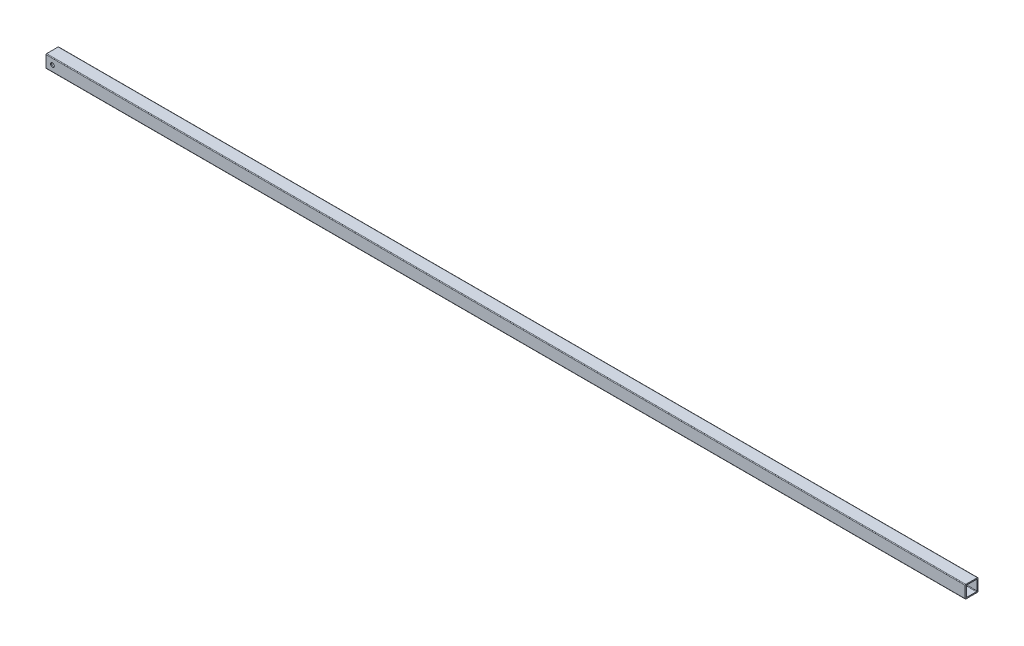
SolidWorks part; units mm, degrees
ref_plane "Front" through (0, 0, 0) normal (0, 0, 1) x (1, 0, 0)
ref_plane "Top" through (0, 0, 0) normal (0, 1, 0) x (1, 0, 0)
ref_plane "Right" through (0, 0, 0) normal (1, 0, 0) x (0, 0, -1)
sketch "Sketch1" plane through (0, 0, 0) normal (1, 0, 0) x (0, 0, -1)
  line L0 (-10.5918, 0) -> (-12.7, 0) construction
  line L1 (11.43, -12.7) -> (-11.43, -12.7) construction
  line L2 (12.7, -11.43) -> (12.7, 11.43) construction
  line L3 (11.43, 12.7) -> (-11.43, 12.7) construction
  line L4 (-12.7, -11.43) -> (-12.7, 11.43) construction
  line L5 (12.7, -12.7) -> (-12.7, 12.7) construction
  line L6 (12.7, 12.7) -> (-12.7, -12.7) construction
  line L7 (9.5326, 10.5918) -> (-9.5326, 10.5918) construction
  line L8 (10.5918, 9.5326) -> (10.5918, -9.5326) construction
  line L9 (9.5326, -10.5918) -> (-9.5326, -10.5918) construction
  line L10 (-10.5918, 9.5326) -> (-10.5918, -9.5326) construction
  line L11 (10.5918, 10.5918) -> (-10.5918, -10.5918) construction
  line L12 (10.5918, -10.5918) -> (-10.5918, 10.5918) construction
  line L13 (0, -10.5918) -> (0, -12.7) construction
  line L14 (10.5918, -9.5326) -> (10.5918, -12.7) construction
  line L15 (10.5918, 0) -> (12.7, 0) construction
  line L16 (10.5918, -12.7) -> (12.7, -12.7) construction
  arc A0 (-9.5326, -10.5918) -> (-10.5918, -9.5326) centre (-9.5326, -9.5326) cw construction
  arc A1 (10.5918, -9.5326) -> (9.5326, -10.5918) centre (9.5326, -9.5326) cw construction
  arc A2 (9.5326, 10.5918) -> (10.5918, 9.5326) centre (9.5326, 9.5326) cw construction
  arc A3 (-9.5326, 10.5918) -> (-10.5918, 9.5326) centre (-9.5326, 9.5326) ccw construction
  arc A4 (11.43, -12.7) -> (12.7, -11.43) centre (11.43, -11.43) ccw construction
  arc A5 (12.7, 11.43) -> (11.43, 12.7) centre (11.43, 11.43) ccw construction
  arc A6 (-11.43, 12.7) -> (-12.7, 11.43) centre (-11.43, 11.43) ccw construction
  arc A7 (-11.43, -12.7) -> (-12.7, -11.43) centre (-11.43, -11.43) cw construction
  point P0 (0, 0)
  point P6 (0, 0)
  dimension "D2" = 1.0592
  dimension "D3" = 1.27
  dimension "Outside Width" = 25.4
  dimension "Ouside Height" = 25.4
  dimension "Inside Height" = 21.1836
  dimension "Wall Thickness" = 2.1082
sketch "Sketch2" plane through (0, 0, 0) normal (0, 0, 1) x (1, 0, 0)
  line L0 (-914.4, 0) -> (914.4, 0) construction
  point P3 (-891.1082, 0)
  point P4 (891.1082, 0)
  dimension "Length" = 1828.8
  dimension "D1" = 23.2918
  dimension "D2" = 23.2918
sketch "Sketch4" plane through (0, 0, 0) normal (1, 0, 0) x (0, 0, -1)
  line L8 (12.7, -11.43) -> (12.7, 11.43)
  line L9 (11.43, 12.7) -> (-11.43, 12.7)
  line L10 (-12.7, -11.43) -> (-12.7, 11.43)
  line L11 (11.43, -12.7) -> (-11.43, -12.7)
  line L12 (10.5918, 9.5326) -> (10.5918, -9.5326)
  line L13 (9.5326, -10.5918) -> (-9.5326, -10.5918)
  line L14 (-10.5918, 9.5326) -> (-10.5918, -9.5326)
  line L15 (9.5326, 10.5918) -> (-9.5326, 10.5918)
  arc A8 (12.7, 11.43) -> (11.43, 12.7) centre (11.43, 11.43) ccw
  arc A9 (-11.43, 12.7) -> (-12.7, 11.43) centre (-11.43, 11.43) ccw
  arc A10 (-12.7, -11.43) -> (-11.43, -12.7) centre (-11.43, -11.43) ccw
  arc A11 (11.43, -12.7) -> (12.7, -11.43) centre (11.43, -11.43) ccw
  arc A12 (9.5326, -10.5918) -> (10.5918, -9.5326) centre (9.5326, -9.5326) ccw
  arc A13 (-10.5918, -9.5326) -> (-9.5326, -10.5918) centre (-9.5326, -9.5326) ccw
  arc A14 (-9.5326, 10.5918) -> (-10.5918, 9.5326) centre (-9.5326, 9.5326) ccw
  arc A15 (10.5918, 9.5326) -> (9.5326, 10.5918) centre (9.5326, 9.5326) ccw
extrude "Boss-Extrude1" add sketch "Sketch4" along normal up to vertex (914.4 mm away) and the other way up to vertex (914.4 mm away)
sketch "Sketch5" plane through (0, 0, 12.7) normal (0, 0, 1) x (1, 0, 0)
  line L0 (-914.4, 11.43) -> (-914.4, -11.43) construction
  line L1 (914.4, 12.7) -> (-914.4, 12.7) construction
  circle A0 centre (-901.7, 0) radius 3.81
  dimension "D2" = 7.62
  dimension "D1" = 12.7
  dimension "D3" = 12.7
extrude "Cut-Extrude1" cut sketch "Sketch5" against normal through all
equation "\"D3@Sketch1\"=\"Outside Width@Sketch1\"*.05"
equation "\"D2@Sketch1\" = \"Inside Height@Sketch1\" * .05"
equation "\"D1@Sketch2\"=\"Outside Width@Sketch1\"-\"Wall Thickness@Sketch1\""
equation "\"D2@Sketch2\"=\"D1@Sketch2\""
